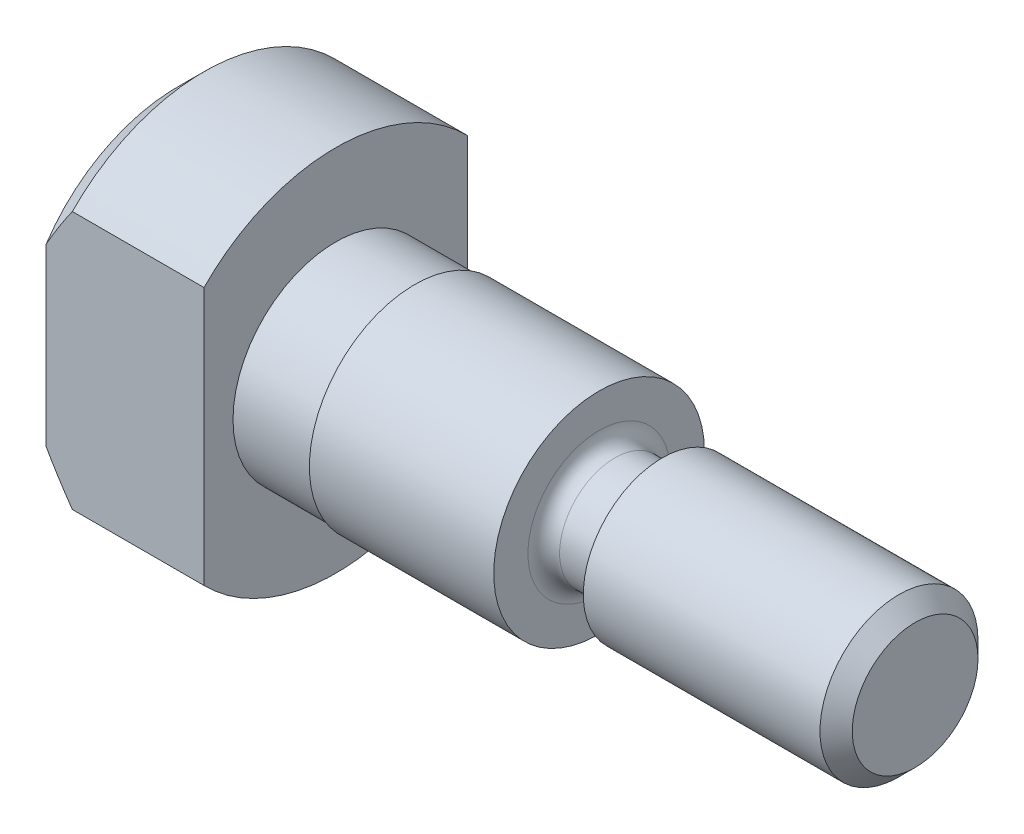
SolidWorks part; units mm, degrees
ref_plane "前基準面" through (0, 0, 0) normal (0, 0, 1) x (1, 0, 0)
ref_plane "上基準面" through (0, 0, 0) normal (0, 1, 0) x (1, 0, 0)
ref_plane "右基準面" through (0, 0, 0) normal (1, 0, 0) x (0, 0, -1)
ref_plane "平面1" through (-3, 0, 0) normal (-1, 0, 0) x (0, -1, 0)
sketch "草圖1" plane through (-3, 0, 0) normal (-1, 0, 0) x (0, -1, 0)
  line L0 (2.4495, 2.5) -> (-2.4495, 2.5)
  line L1 (-2.4495, -2.5) -> (2.4495, -2.5)
  arc A0 (-2.4495, 2.5) -> (-2.4495, -2.5) centre (0, 0) ccw
  arc A1 (2.4495, -2.5) -> (2.4495, 2.5) centre (0, 0) ccw
extrude "填料-伸長1" add sketch "草圖1" against normal blind 3
sketch "草圖2" plane through (0, 0, 0) normal (0, 0, 1) x (1, 0, 0)
  line L0 (0, 1.95) -> (0, 0)
  line L1 (0, 0) -> (11, 0)
  line L2 (11, 0) -> (11, 1.5)
  line L3 (11, 1.5) -> (6.2, 1.5)
  line L4 (6.2, 1.5) -> (6.2, 1.05)
  line L5 (6.2, 1.05) -> (5, 1.05)
  line L6 (5, 1.05) -> (5, 2)
  line L7 (5, 2) -> (1.5, 2)
  line L8 (1.5, 2) -> (1.5, 1.95)
  line L9 (1.5, 1.95) -> (0, 1.95)
  line L10 (0, 0) -> (11, 0) construction
revolve "旋轉1" add sketch "草圖2" angle 360 about L10
chamfer "導角1" distance 0.3065 angle 45 1 edges at (11, 0, -1.5)
chamfer "導角2" distance 0.5 angle 45 2 edges at (-3, 3.5, 0) (-3, -3.5, 0)
fillet "圓角1" radius 0.3 2 edges at (5, 0, -1.05) (6.2, 0, -1.05)
